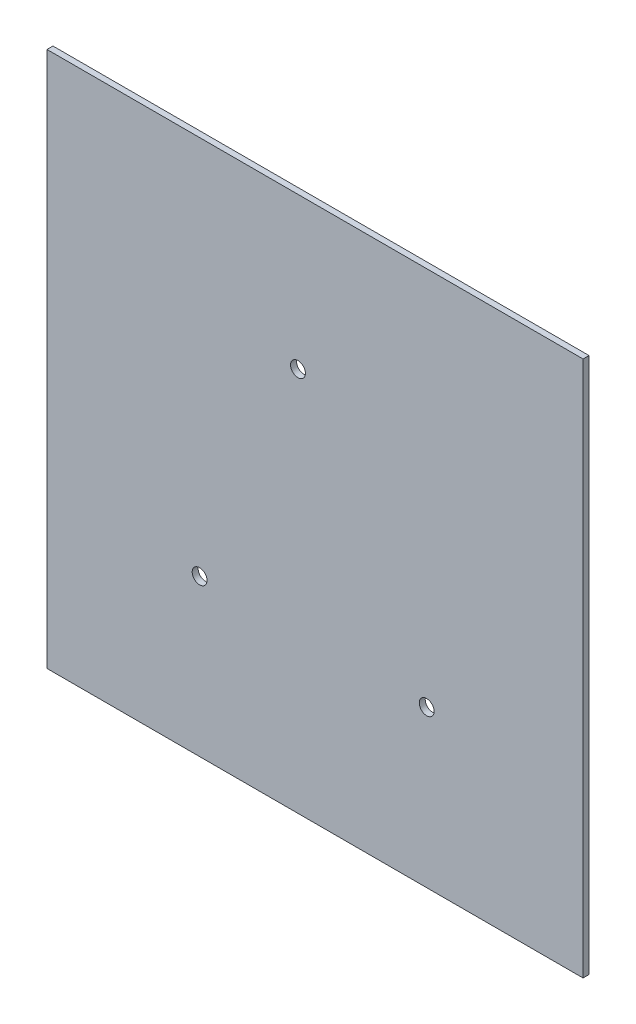
SolidWorks part; units mm, degrees
ref_plane "Front Plane" through (0, 0, 0) normal (0, 0, 1) x (1, 0, 0)
ref_plane "Top Plane" through (0, 0, 0) normal (0, 1, 0) x (1, 0, 0)
ref_plane "Right Plane" through (0, 0, 0) normal (1, 0, 0) x (0, 0, -1)
sketch "Sketch1" plane through (0, 0, 0) normal (0, 0, 1) x (1, 0, 0)
  line L0 (66.675, -66.675) -> (-161.925, 161.925) construction
  line L1 (66.675, 161.925) -> (-161.925, 161.925)
  line L2 (66.675, 161.925) -> (66.675, -66.675)
  line L3 (66.675, -66.675) -> (-161.925, -66.675)
  line L4 (-161.925, 161.925) -> (-161.925, -66.675)
  line L5 (66.675, 161.925) -> (-161.925, -66.675) construction
  line L6 (-47.625, -47.625) -> (47.625, -47.625) construction
  line L7 (47.625, -47.625) -> (47.625, 47.625) construction
  circle A0 centre (0, 0) radius 3.175
  circle A1 centre (-96.8397, -0.0738) radius 3.175
  circle A2 centre (-54.891, 97.3901) radius 3.175
  dimension "D5" = 6.35
  dimension "D1" = 228.6
  dimension "D2" = 228.6
  dimension "D3" = 19.05
  dimension "D4" = 19.05
extrude "Boss-Extrude1" add sketch "Sketch1" along normal blind 2.54
